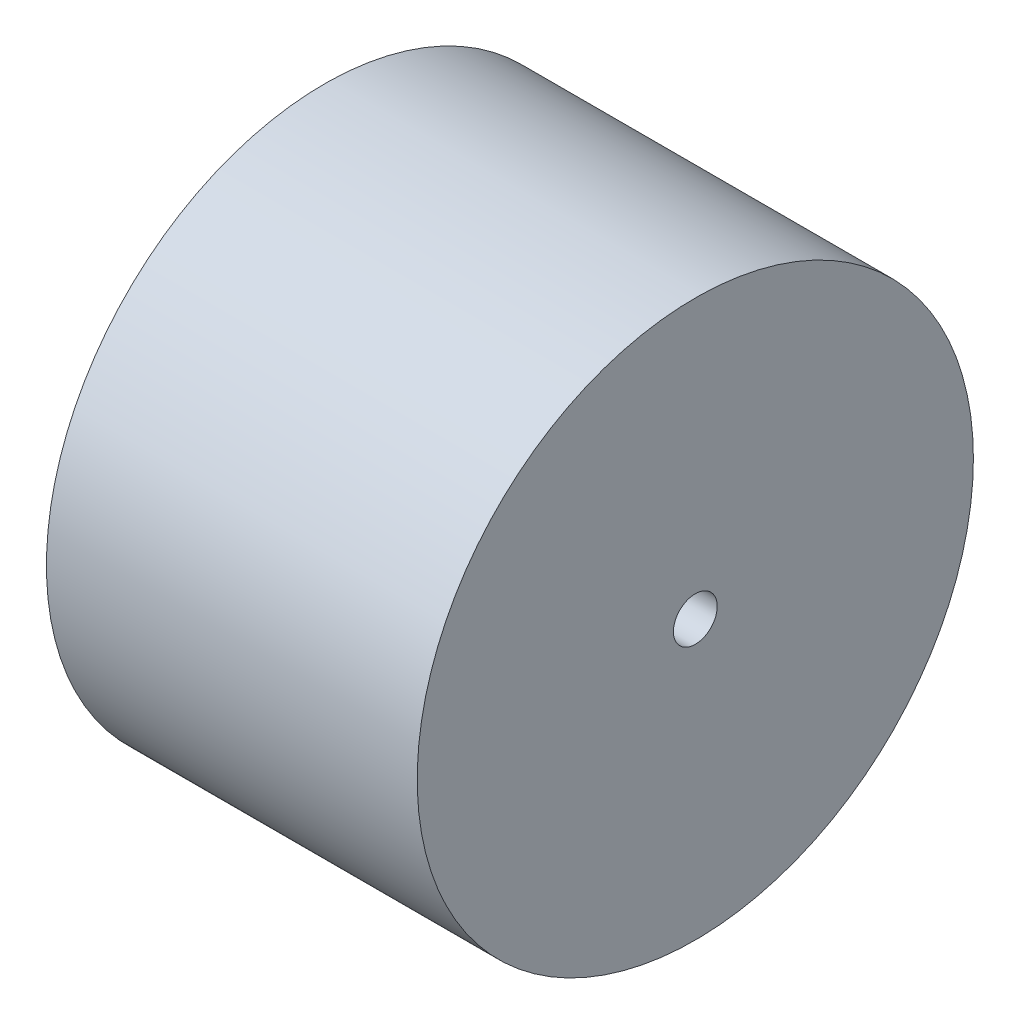
SolidWorks part; units mm, degrees
ref_plane "Front Plane" through (0, 0, 0) normal (0, 0, 1) x (1, 0, 0)
ref_plane "Top Plane" through (0, 0, 0) normal (0, 1, 0) x (1, 0, 0)
ref_plane "Right Plane" through (0, 0, 0) normal (1, 0, 0) x (0, 0, -1)
sketch "Sketch1" plane through (0, 0, 0) normal (1, 0, 0) x (0, 0, -1)
  circle A0 centre (0, 0) radius 19.05
  circle A1 centre (0, 0) radius 1.5
  dimension "D1" = 38.1
  dimension "D2" = 3
extrude "Boss-Extrude1" add sketch "Sketch1" along normal mid plane 25.4 contours A0 A1
